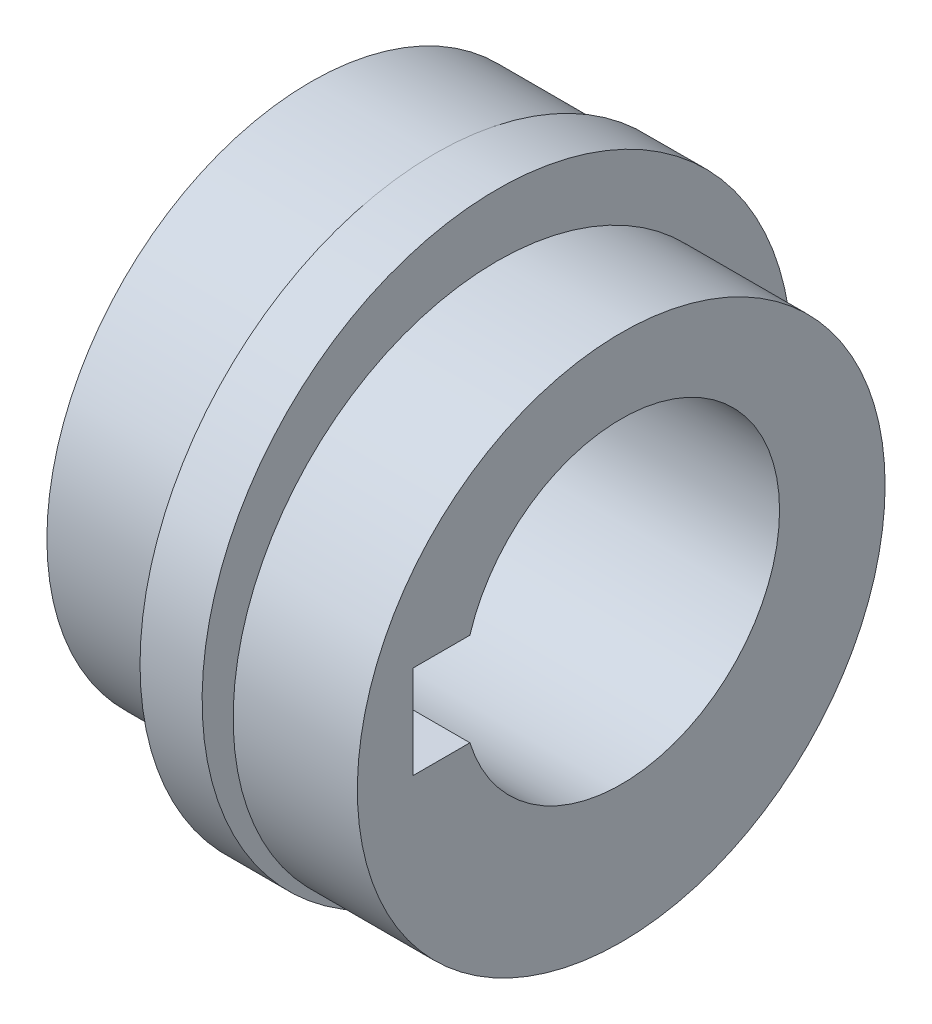
SolidWorks part; units mm, degrees
ref_plane "Front Plane" through (0, 0, 0) normal (1, 0, 0) x (0, 1, 0)
ref_plane "Top Plane" through (0, 0, 0) normal (0, 0, 1) x (0, 1, 0)
ref_plane "Right Plane" through (0, 0, 0) normal (0, 1, 0) x (-1, 0, 0)
sketch "Sketch1" plane through (0, 0, 0) normal (1, 0, 0) x (0, 1, 0)
  circle A0 centre (0, 0) radius 9.5
  dimension "D1" = 19
extrude "Boss-Extrude1" add sketch "Sketch1" along normal mid plane 2
sketch "Sketch2" plane through (1, 0, 0) normal (1, 0, 0) x (0, 1, 0)
  circle A0 centre (-1, 0) radius 8.5
  point P2 (0, 0)
  dimension "D1" = 17
  dimension "D2" = 1
extrude "Boss-Extrude3" add sketch "Sketch2" along normal blind 4 contours A0
sketch "Sketch3" plane through (-1, 0, 0) normal (-1, 0, 0) x (0, -1, 0)
  circle A0 centre (-1, 0) radius 8.5
  point P2 (0, 0)
  dimension "D1" = 17
  dimension "D2" = 1
extrude "Boss-Extrude4" add sketch "Sketch3" along normal blind 4
sketch "Sketch4" plane through (5, 0, 0) normal (1, 0, 0) x (0, 1, 0)
  line L0 (-1.5, 4.8744) -> (-1.5, 6.7)
  line L1 (-1.5, 6.7) -> (1.5, 6.7)
  line L2 (1.5, 6.7) -> (1.5, 4.8744)
  line L3 (0, 5.1) -> (0, 6.7) construction
  circle A0 centre (0, 0) radius 5.1 construction
  arc A1 (-1.5, 4.8744) -> (1.5, 4.8744) centre (0, 0) ccw
  point P5 (0, 6.7)
  point P11 (2.3757, 4.5129)
  point P12 (0, 0)
  dimension "D1" = 10.2
  dimension "D2" = 3
  dimension "D3" = 1.6
extrude "Cut-Extrude1" cut sketch "Sketch4" against normal through all contours A1 L2 L1 L0
